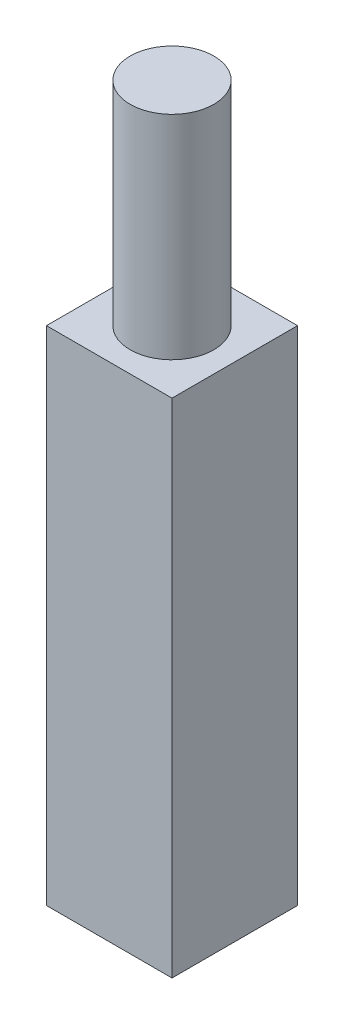
SolidWorks part; units mm, degrees
material "Stainless Steel (ferritic)"
ref_plane "Front Plane" through (0, 0, 0) normal (0, 0, 1) x (1, 0, 0)
ref_plane "Top Plane" through (0, 0, 0) normal (0, 1, 0) x (1, 0, 0)
ref_plane "Right Plane" through (0, 0, 0) normal (1, 0, 0) x (0, 0, -1)
sketch "Sketch1" plane through (0, 0, 0) normal (0, 1, 0) x (1, 0, 0)
  line L1 (-7.5, 7.5) -> (7.5, 7.5)
  line L2 (-7.5, 7.5) -> (-7.5, -7.5)
  line L3 (-7.5, -7.5) -> (7.5, -7.5)
  line L4 (7.5, 7.5) -> (7.5, -7.5)
  line L5 (-7.5, 7.5) -> (7.5, -7.5) construction
  line L6 (-7.5, -7.5) -> (7.5, 7.5) construction
  point P0 (0, 0)
  dimension "D1" = 15
  dimension "D2" = 15
extrude "Boss-Extrude1" add sketch "Sketch1" along normal blind 60
sketch "Sketch2" plane through (0, 60, 0) normal (0, 1, 0) x (1, 0, 0)
  circle A0 centre (0, 0) radius 5
  dimension "D1" = 10
extrude "Boss-Extrude2" add sketch "Sketch2" along normal blind 25.4
equation "\"D2@Sketch1\"=\"D1@Sketch1\""
